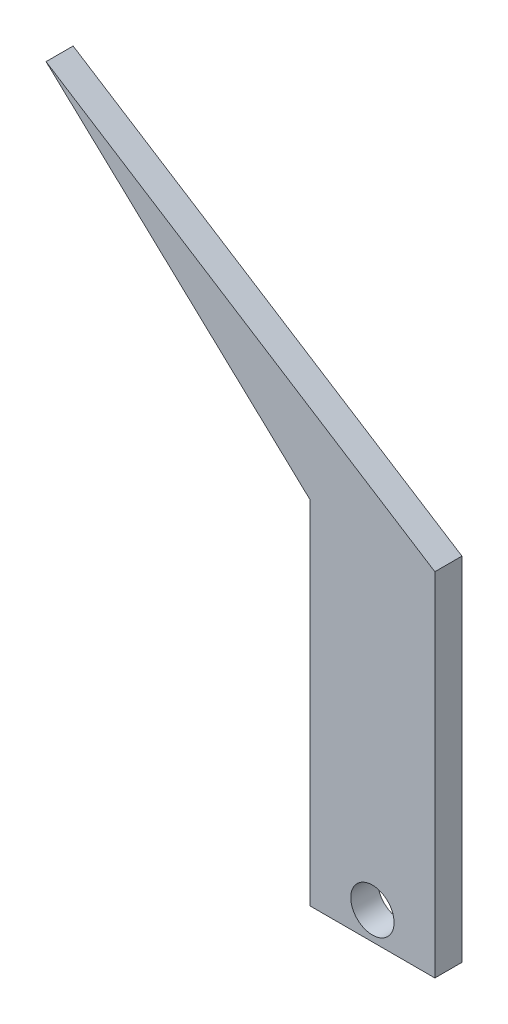
SolidWorks part; units mm, degrees
ref_plane "前视基准面" through (0, 0, 0) normal (0, 0, 1) x (1, 0, 0)
ref_plane "上视基准面" through (0, 0, 0) normal (0, 1, 0) x (1, 0, 0)
ref_plane "右视基准面" through (0, 0, 0) normal (1, 0, 0) x (0, 0, -1)
other "Configuration Table"
sketch "草图1" plane through (0, 0, 0) normal (0, 0, 1) x (1, 0, 0)
  line L0 (0, 0) -> (0, 65)
  line L5 (23.07, 65) -> (23.07, 0)
  line L6 (23.07, 0) -> (0, 0)
  line L10 (23.07, 65) -> (-48.7555, 110.6939)
  line L11 (-48.7555, 110.6939) -> (0, 65)
  point P3 (-37.2785, 112.1038)
  point P5 (-48.7555, 110.6939)
  dimension "D2" = 23.07
extrude "凸台-拉伸1" add sketch "草图1" along normal blind 5
sketch "草图2" plane through (0, 0, 5) normal (0, 0, 1) x (1, 0, 0)
  line L0 (11.535, 0) -> (11.535, 38.4773) construction
  line L1 (0, 0) -> (23.07, 0) construction
  line L2 (0, 65) -> (0, 0) construction
  line L3 (23.07, 32.5) -> (0, 32.5) construction
  line L4 (23.07, 0) -> (23.07, 65) construction
  circle A0 centre (11.535, 5.1043) radius 4
  circle A1 centre (11.535, 59.8957) radius 4
extrude "切除-拉伸1" cut sketch "草图2" against normal blind 5
sketch "草图3" plane through (0, 0, 5) normal (0, 0, 1) x (1, 0, 0)
  circle A0 centre (11.535, 59.8957) radius 4
extrude "凸台-拉伸2" add sketch "草图3" against normal blind 5
